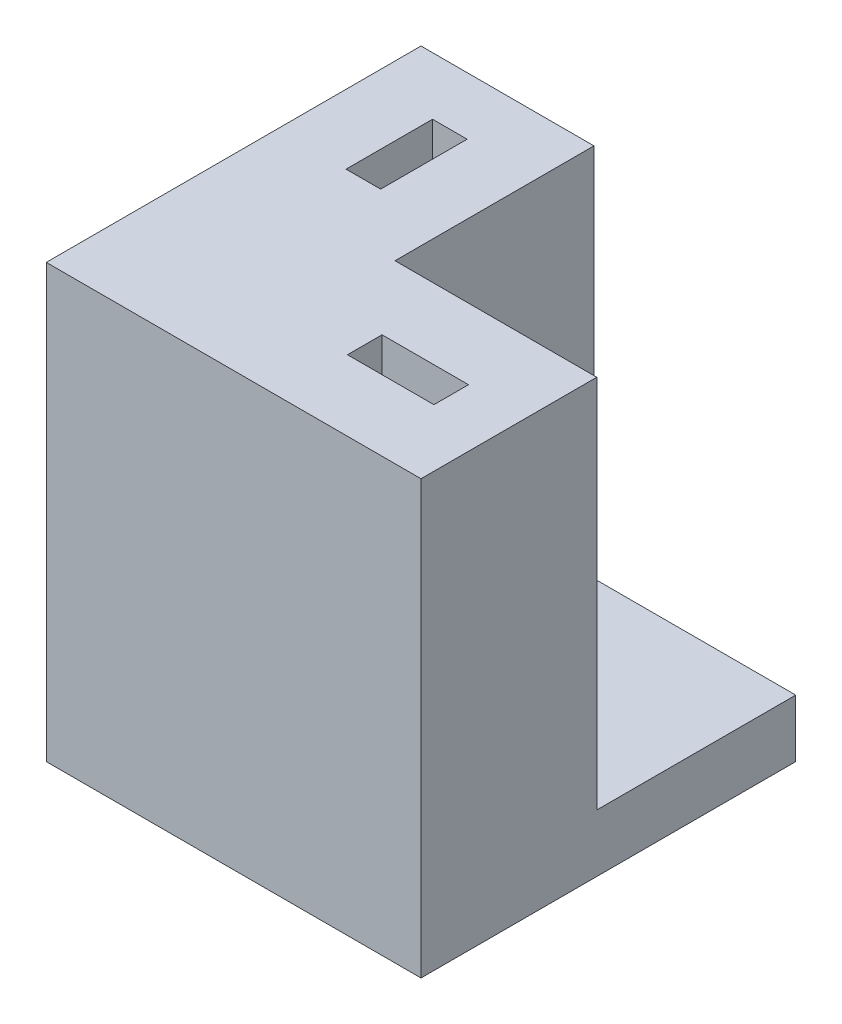
SolidWorks part; units mm, degrees
ref_plane "Front Plane" through (0, 0, 0) normal (0, 0, 1) x (1, 0, 0)
ref_plane "Top Plane" through (0, 0, 0) normal (0, 1, 0) x (1, 0, 0)
ref_plane "Right Plane" through (0, 0, 0) normal (1, 0, 0) x (0, 0, -1)
sketch "Sketch3" plane through (0, 0, 0) normal (0, 1, 0) x (1, 0, 0)
  line L1 (-8.255, -8.255) -> (8.255, -8.255)
  line L2 (-8.255, -8.255) -> (-8.255, 8.255)
  line L3 (-8.255, 8.255) -> (8.255, 8.255)
  line L4 (8.255, -8.255) -> (8.255, 8.255)
  line L5 (-8.255, -8.255) -> (8.255, 8.255) construction
  line L6 (-8.255, 8.255) -> (8.255, -8.255) construction
  point P0 (0, 0)
  dimension "D1" = 16.51
  dimension "D2" = 16.51
extrude "Boss-Extrude2" add sketch "Sketch3" along normal blind 19.05
sketch "Sketch4" plane through (0, 19.05, 0) normal (0, 1, 0) x (1, 0, 0)
  line L0 (8.255, 8.255) -> (0, 8.255)
  line L1 (8.255, 8.255) -> (-8.255, 8.255) construction
  line L2 (0, 8.255) -> (0, 0)
  line L3 (0, 0) -> (8.255, 0)
  line L4 (8.255, -8.255) -> (8.255, 8.255) construction
  line L5 (8.255, 0) -> (8.255, 8.255)
sketch "Sketch5" plane through (0, 0, 0) normal (0, -1, 0) x (1, 0, 0)
  line L1 (0, 0) -> (-8.255, 8.255) construction
  circle A1 centre (-4.1275, 4.1275) radius 2.54
  dimension "D1" = 5.08
extrude "Cut-Extrude2" cut sketch "Sketch5" against normal blind 5.715
sketch "Sketch6" plane through (0, 19.05, 0) normal (0, 1, 0) x (1, 0, 0)
  line L0 (8.255, -0.5109) -> (-0.635, -0.5109)
  line L1 (8.255, -8.255) -> (8.255, 8.255) construction
  line L2 (-0.635, -0.5109) -> (-0.635, 8.255)
  line L3 (8.255, 8.255) -> (-8.255, 8.255) construction
  line L4 (8.255, 8.255) -> (0, 8.255) construction
  line L5 (-0.635, 8.255) -> (8.255, 8.255)
  line L6 (8.255, 8.255) -> (8.255, -0.5109)
  dimension "D1" = 8.7659
  dimension "D2" = 8.89
extrude "Cut-Extrude3" cut sketch "Sketch6" against normal blind 16.51
sketch "Sketch7" plane through (0, 19.05, 0) normal (0, 1, 0) x (1, 0, 0)
  line L0 (-4.445, 8.255) -> (-4.445, -8.255) construction
  line L1 (-0.635, 8.255) -> (-8.255, 8.255) construction
  line L2 (-8.255, -8.255) -> (8.255, -8.255) construction
  line L3 (8.255, -4.383) -> (-8.255, -4.383) construction
  line L4 (8.255, -8.255) -> (8.255, -0.5109) construction
  line L5 (-8.255, 8.255) -> (-8.255, -8.255) construction
  line L7 (-5.207, 1.905) -> (-3.683, 1.905)
  line L8 (-5.207, 1.905) -> (-5.207, 5.715)
  line L9 (-5.207, 5.715) -> (-3.683, 5.715)
  line L10 (-3.683, 1.905) -> (-3.683, 5.715)
  line L11 (-5.207, 1.905) -> (-3.683, 5.715) construction
  line L12 (-5.207, 5.715) -> (-3.683, 1.905) construction
  line L13 (1.905, -5.145) -> (5.715, -5.145)
  line L14 (1.905, -5.145) -> (1.905, -3.621)
  line L15 (1.905, -3.621) -> (5.715, -3.621)
  line L16 (5.715, -5.145) -> (5.715, -3.621)
  line L17 (1.905, -5.145) -> (5.715, -3.621) construction
  line L18 (1.905, -3.621) -> (5.715, -5.145) construction
  point P12 (-4.445, 3.81)
  point P17 (3.81, -4.383)
  dimension "D1" = 1.524
  dimension "D2" = 3.81
  dimension "D3" = 2.54
  dimension "D4" = 3.81
  dimension "D5" = 1.524
  dimension "D6" = 2.54
extrude "Cut-Extrude4" cut sketch "Sketch7" against normal blind 2.54
